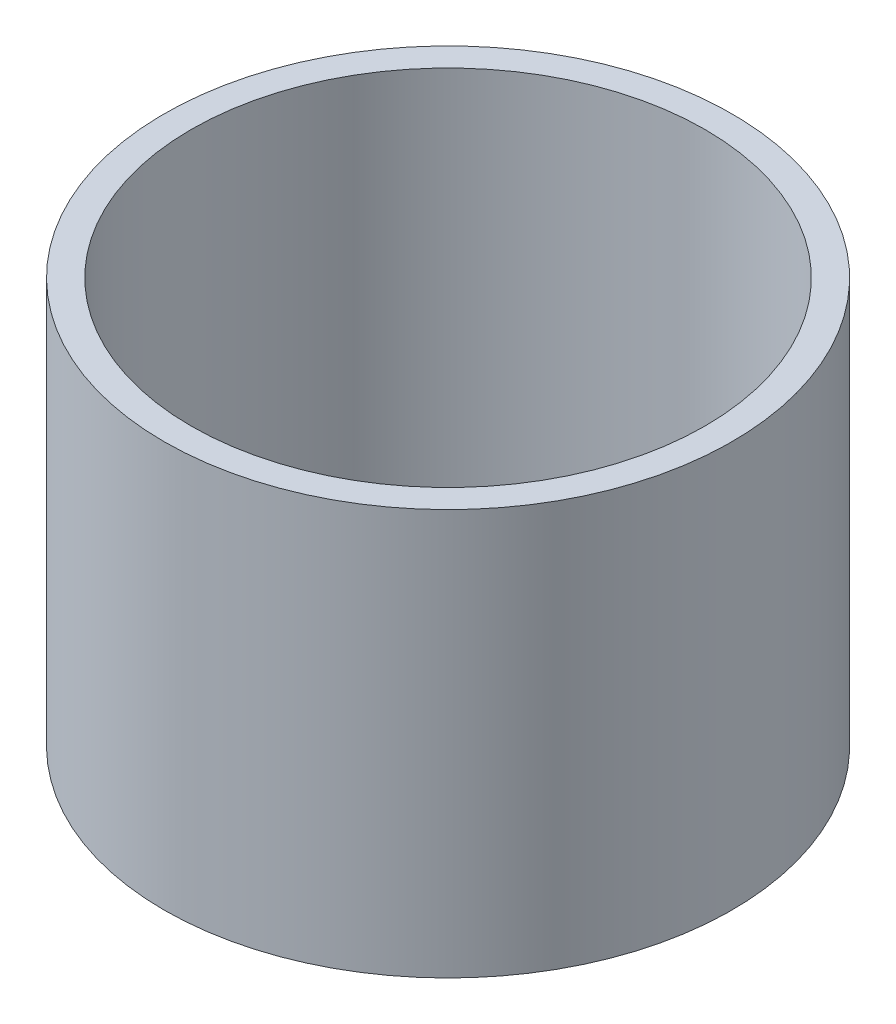
SolidWorks part; units mm, degrees
ref_plane "Front Plane" through (0, 0, 0) normal (0, 0, 1) x (1, 0, 0)
ref_plane "Top Plane" through (0, 0, 0) normal (0, 1, 0) x (1, 0, 0)
ref_plane "Right Plane" through (0, 0, 0) normal (1, 0, 0) x (0, 0, -1)
sketch "Sketch1" plane through (0, 0, 0) normal (0, 1, 0) x (1, 0, 0)
  circle A2 centre (0, 0) radius 1.05
  circle A3 centre (0, 0) radius 0.95
extrude "Boss-Extrude1" add sketch "Sketch1" along normal blind 1.5
